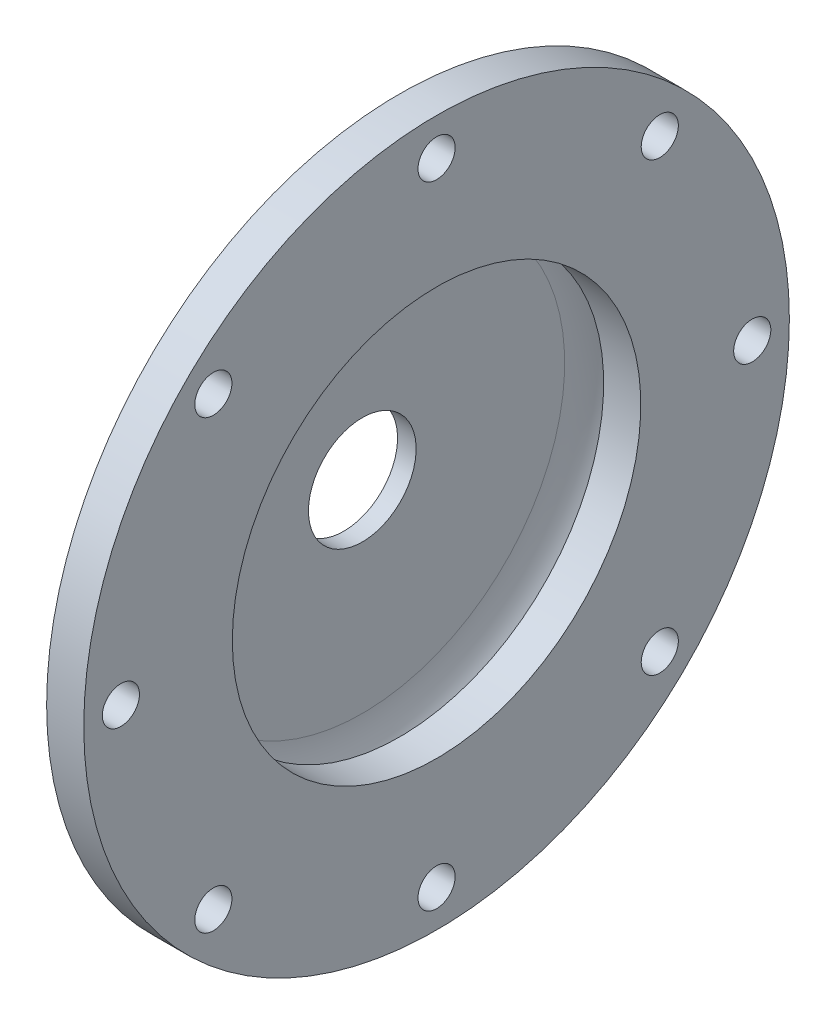
SolidWorks part; units mm, degrees
ref_plane "Front Plane" through (0, 0, 0) normal (0, 0, 1) x (1, 0, 0)
ref_plane "Top Plane" through (0, 0, 0) normal (0, 1, 0) x (1, 0, 0)
ref_plane "Right Plane" through (0, 0, 0) normal (1, 0, 0) x (0, 0, -1)
sketch "Sketch2" plane through (0, 0, 0) normal (0, 0, 1) x (1, 0, 0)
  line L0 (-978.5278, 0) -> (47947.8619, 0) construction
  line L1 (0, 34.925) -> (6.35, 34.925)
  line L2 (0, 34.925) -> (0, 60.325)
  line L3 (0, 60.325) -> (6.35, 60.325)
  line L4 (6.35, 34.925) -> (6.35, 60.325)
  line L5 (-6.35, 34.6075) -> (-6.35, 9.2075)
  line L6 (-6.35, 9.2075) -> (-9.525, 9.2075)
  line L7 (-9.525, 9.2075) -> (-9.525, 34.6075)
  line L8 (-6.35, 20.164) -> (-6.35, -1.8331) construction
  line L9 (0, 33.3375) -> (-6.35, 33.3375) construction
  line L10 (-6.35, 7.9375) -> (-44.45, 7.9375) construction
  arc A0 (-6.35, 34.6075) -> (0, 44.45) centre (4.4529, 34.6075) cw
  arc A1 (-9.525, 34.6075) -> (0, 47.625) centre (4.1328, 34.6075) cw
  point P9 (0, 47.625)
  point P16 (0, 42.1931)
  point P19 (0, 44.9203)
  point P22 (0, 47.625)
  point P23 (-12.7, 30.3149)
  point P24 (0, 42.3749)
  point P25 (-12.7, 31.1028)
  point P27 (0, 47.625)
  point P28 (-12.7, 34.6075)
  point P29 (0, 0)
  point P32 (-11.1125, 33.6387)
  point P33 (0, 0)
  point P34 (-11.1125, 34.0946)
  point P35 (0, 0)
  dimension "D7" = 1.27
  dimension "D1" = 60.325
  dimension "D2" = 6.35
  dimension "D3" = 25.4
  dimension "D4" = 3.175
  dimension "D5" = 1.27
  dimension "D6" = 3.175
revolve "Revolve1" add sketch "Sketch2" angle 360 about L0
extrude "Cut-Extrude1" cut sketch "Sketch3" against normal through all both and the other way through all
sketch "Sketch3" plane through (0, 0, 0) normal (-1, 0, 0) x (0, 0, 1)
  line L0 (0, 47.625) -> (0, 60.325) construction
  circle A0 centre (0, 53.975) radius 3.175
  circle A3 centre (38.1661, 38.1661) radius 3.175
  circle A4 centre (53.975, 0) radius 3.175
  circle A5 centre (38.1661, -38.1661) radius 3.175
  circle A6 centre (0, -53.975) radius 3.175
  circle A7 centre (-38.1661, -38.1661) radius 3.175
  circle A8 centre (-53.975, 0) radius 3.175
  circle A9 centre (-38.1661, 38.1661) radius 3.175
  point P3 (0, 0)
  point P26 (0, 0)
